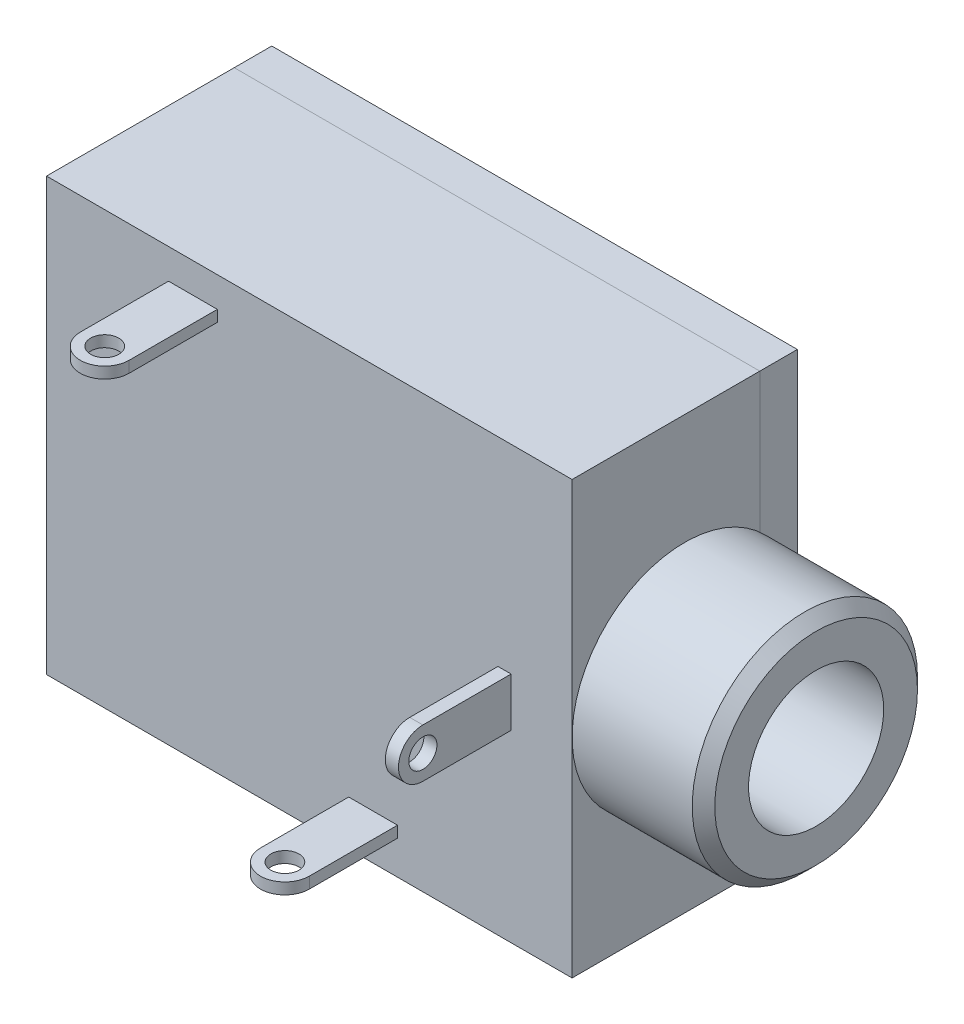
SolidWorks part; units mm, degrees
ref_plane "Front Plane" through (0, 0, 0) normal (0, 0, 1) x (1, 0, 0)
ref_plane "Top Plane" through (0, 0, 0) normal (0, 1, 0) x (1, 0, 0)
ref_plane "Right Plane" through (0, 0, 0) normal (1, 0, 0) x (0, 0, -1)
ref_plane "Plane1" through (0, 0, -3) normal (0, 0, -1) x (-1, 0, 0)
sketch "Sketch1" plane through (0, 0, -3) normal (0, 0, -1) x (-1, 0, 0)
  line L0 (3.5, 5.95) -> (3.5, -5.55)
  line L1 (3.5, -5.55) -> (17.5, -5.55)
  line L2 (17.5, -5.55) -> (17.5, 5.95)
  line L3 (17.5, 5.95) -> (3.5, 5.95)
extrude "Boss-Extrude1" add sketch "Sketch1" against normal blind 1
ref_plane "Plane2" through (0, 0, 3) normal (0, 0, 1) x (1, 0, 0)
sketch "Sketch6" plane through (0, 0, 3) normal (0, 0, 1) x (1, 0, 0)
  line L0 (-17.5, 5.95) -> (-17.5, -5.55)
  line L1 (-17.5, -5.55) -> (-3.5, -5.55)
  line L2 (-3.5, -5.55) -> (-3.5, 5.95)
  line L3 (-3.5, 5.95) -> (-17.5, 5.95)
extrude "Boss-Extrude2" add sketch "Sketch6" against normal blind 5 separate body
ref_plane "Plane3" through (-3.5, 0, 0) normal (1, 0, 0) x (0, 0, -1)
sketch "Sketch12" plane through (-3.5, 0, 0) normal (1, 0, 0) x (0, 0, -1)
  circle A0 centre (0, 0) radius 3
extrude "Boss-Extrude3" add sketch "Sketch12" along normal blind 3.5 separate body
ref_plane "Plane4" through (0, 5.15, 0) normal (0, 1, 0) x (1, 0, 0)
sketch "Sketch19" plane through (0, 5.15, 0) normal (0, 1, 0) x (1, 0, 0)
  line L0 (-14.25, -3) -> (-14.25, -5.35)
  line L1 (-12.95, -5.35) -> (-12.95, -3)
  line L2 (-12.95, -3) -> (-14.25, -3)
  arc A0 (-14.25, -5.35) -> (-12.95, -5.35) centre (-13.6, -5.35) ccw
extrude "Boss-Extrude4" add sketch "Sketch19" against normal blind 0.3 separate body
ref_plane "Plane5" through (-5.475, 0, 0) normal (-1, 0, 0) x (0, 0, 1)
sketch "Sketch27" plane through (-5.475, 0, 0) normal (-1, 0, 0) x (0, 0, 1)
  line L0 (3, -0.65) -> (5.35, -0.65)
  line L1 (5.35, 0.65) -> (3, 0.65)
  line L2 (3, 0.65) -> (3, -0.65)
  arc A0 (5.35, -0.65) -> (5.35, 0.65) centre (5.35, 0) ccw
extrude "Boss-Extrude5" add sketch "Sketch27" against normal blind 0.35 separate body
ref_plane "Plane6" through (0, -4.35, 0) normal (0, 1, 0) x (1, 0, 0)
sketch "Sketch36" plane through (0, -4.35, 0) normal (0, 1, 0) x (1, 0, 0)
  line L0 (-9.45, -3) -> (-9.45, -5.35)
  line L1 (-8.15, -5.35) -> (-8.15, -3)
  line L2 (-8.15, -3) -> (-9.45, -3)
  arc A0 (-9.45, -5.35) -> (-8.15, -5.35) centre (-8.8, -5.35) ccw
extrude "Boss-Extrude6" add sketch "Sketch36" against normal blind 0.3 separate body
hole_wizard "Ø0.75 (0.75) Diameter Hole1" positions "Sketch38" profile "Sketch37" hole size "Ø0.75" standard "ANSI Metric"
sketch "Sketch38" plane through (0, -4.35, 0) normal (0, 1, 0) x (1, 0, 0)
  point P0 (-8.8, -5.35)
sketch "Sketch37" plane through (-8.8, -4.35, 5.35) normal (1, 0, 0) x (0, 0, 1)
  line L0 (0, 0) -> (0, 1.2)
  line L1 (0, 1.2) -> (0.375, 1.2)
  line L2 (0.375, 1.2) -> (0.375, 0)
  line L5 (0.375, 0) -> (0, 0)
  line L10 (0, 1.2) -> (-0.375, 1.2) construction
  line L11 (0, -6.35) -> (0, 107.95) construction
  dimension "Hole Dia." = 0.75
  dimension "Hole Depth" = 1.2
  dimension "Drill Angle" = 180
hole_wizard "Ø0.75 (0.75) Diameter Hole2" positions "Sketch40" profile "Sketch39" hole size "Ø0.75" standard "ANSI Metric"
sketch "Sketch40" plane through (-5.475, 0, 0) normal (-1, 0, 0) x (0, 0, 1)
  point P0 (5.35, 0)
sketch "Sketch39" plane through (-5.475, 0, 5.35) normal (0, 1, 0) x (0, 0, 1)
  line L0 (0, 0) -> (0, 5.475)
  line L1 (0, 5.475) -> (0.375, 5.475)
  line L2 (0.375, 5.475) -> (0.375, 0)
  line L5 (0.375, 0) -> (0, 0)
  line L10 (0, 5.475) -> (-0.375, 5.475) construction
  line L11 (0, -6.35) -> (0, 107.95) construction
  dimension "Hole Dia." = 0.75
  dimension "Hole Depth" = 5.475
  dimension "Drill Angle" = 180
hole_wizard "Ø0.75 (0.75) Diameter Hole3" positions "Sketch42" profile "Sketch41" hole size "Ø0.75" standard "ANSI Metric"
sketch "Sketch42" plane through (0, 4.85, 0) normal (0, -1, 0) x (-1, 0, 0)
  point P0 (13.6, -5.35)
sketch "Sketch41" plane through (-13.6, 4.85, 5.35) normal (1, 0, 0) x (0, 0, -1)
  line L0 (0, 0) -> (0, 1.1)
  line L1 (0, 1.1) -> (0.375, 1.1)
  line L2 (0.375, 1.1) -> (0.375, 0)
  line L5 (0.375, 0) -> (0, 0)
  line L10 (0, 1.1) -> (-0.375, 1.1) construction
  line L11 (0, -6.35) -> (0, 107.95) construction
  dimension "Hole Dia." = 0.75
  dimension "Hole Depth" = 1.1
  dimension "Drill Angle" = 180
hole_wizard "Ø3.6 (3.6) Diameter Hole1" positions "Sketch44" profile "Sketch43" hole size "Ø3.6" standard "ANSI Metric"
sketch "Sketch44" plane through (0, 0, 0) normal (1, 0, 0) x (0, 0, -1)
  point P0 (0, 0)
sketch "Sketch43" plane through (0, 0, 0) normal (0, 1, 0) x (0, 0, -1)
  line L0 (0, 0) -> (0, 3.5)
  line L1 (0, 3.5) -> (1.8, 3.5)
  line L2 (1.8, 3.5) -> (1.8, 0)
  line L5 (1.8, 0) -> (0, 0)
  line L10 (0, 3.5) -> (-1.8, 3.5) construction
  line L11 (0, -6.35) -> (0, 107.95) construction
  dimension "Hole Dia." = 3.6
  dimension "Hole Depth" = 3.5
  dimension "Drill Angle" = 180
chamfer "Chamfer1" distance 0.3 angle 45 1 edges at (0, 0, -3)
